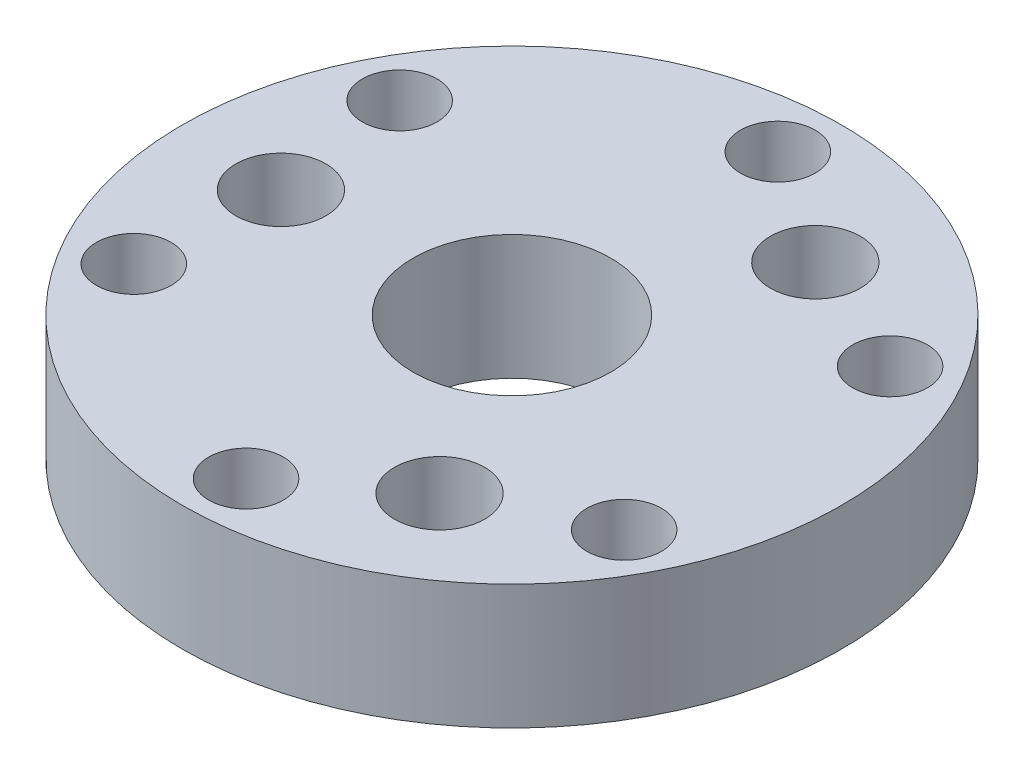
SolidWorks part; units mm, degrees
material "Aleación 6061"
ref_plane "Alzado" through (0, 0, 0) normal (0, 0, 1) x (1, 0, 0)
ref_plane "Planta" through (0, 0, 0) normal (0, 1, 0) x (1, 0, 0)
ref_plane "Vista lateral" through (0, 0, 0) normal (1, 0, 0) x (0, 0, -1)
sketch "Croquis5" plane through (0, 0, 0) normal (0, 1, 0) x (1, 0, 0)
  circle A0 centre (152.4, -171.45) radius 15
  dimension "D1" = 30
  dimension "D2" = 152.4
  dimension "D3" = 171.45
extrude "Disco" add sketch "Croquis5" along normal blind 5.67 from offset 3.175
sketch "Croquis6" plane through (0, 0, 0) normal (0, 1, 0) x (1, 0, 0)
  circle A0 centre (163.4163, -177.3569) radius 1.7
  circle A1 centre (152.7926, -183.9438) radius 1.7
  circle A2 centre (141.7763, -178.0369) radius 1.7
  circle A3 centre (141.3837, -165.5431) radius 1.7
  circle A4 centre (152.0074, -158.9562) radius 1.7
  circle A5 centre (163.0237, -164.8631) radius 1.7
  circle A6 centre (157.7749, -180.1189) radius 2.05
  circle A7 centre (142.205, -171.7704) radius 2.05
  circle A8 centre (157.22, -162.4607) radius 2.05
  circle A9 centre (152.4, -171.45) radius 4.5
  dimension "D1" = 3.4
  dimension "D2" = 3.4
  dimension "D3" = 3.4
  dimension "D4" = 3.4
  dimension "D5" = 3.4
  dimension "D6" = 3.4
  dimension "D7" = 4.1
  dimension "D8" = 4.1
  dimension "D9" = 4.1
  dimension "D10" = 9
  dimension "D11" = 163.4163
  dimension "D12" = 177.3569
  dimension "D13" = 152.7926
  dimension "D14" = 183.9438
  dimension "D15" = 141.7763
  dimension "D16" = 178.0369
  dimension "D17" = 141.3837
  dimension "D18" = 165.5431
  dimension "D19" = 152.0074
  dimension "D20" = 158.9562
  dimension "D21" = 163.0237
  dimension "D22" = 164.8631
  dimension "D23" = 157.7749
  dimension "D24" = 180.1189
  dimension "D25" = 142.205
  dimension "D26" = 171.7704
  dimension "D27" = 157.22
  dimension "D28" = 162.4607
  dimension "D29" = 152.4
  dimension "D30" = 171.45
extrude "Barrenos" cut sketch "Croquis6" along normal blind 5.67 from offset 3.175
